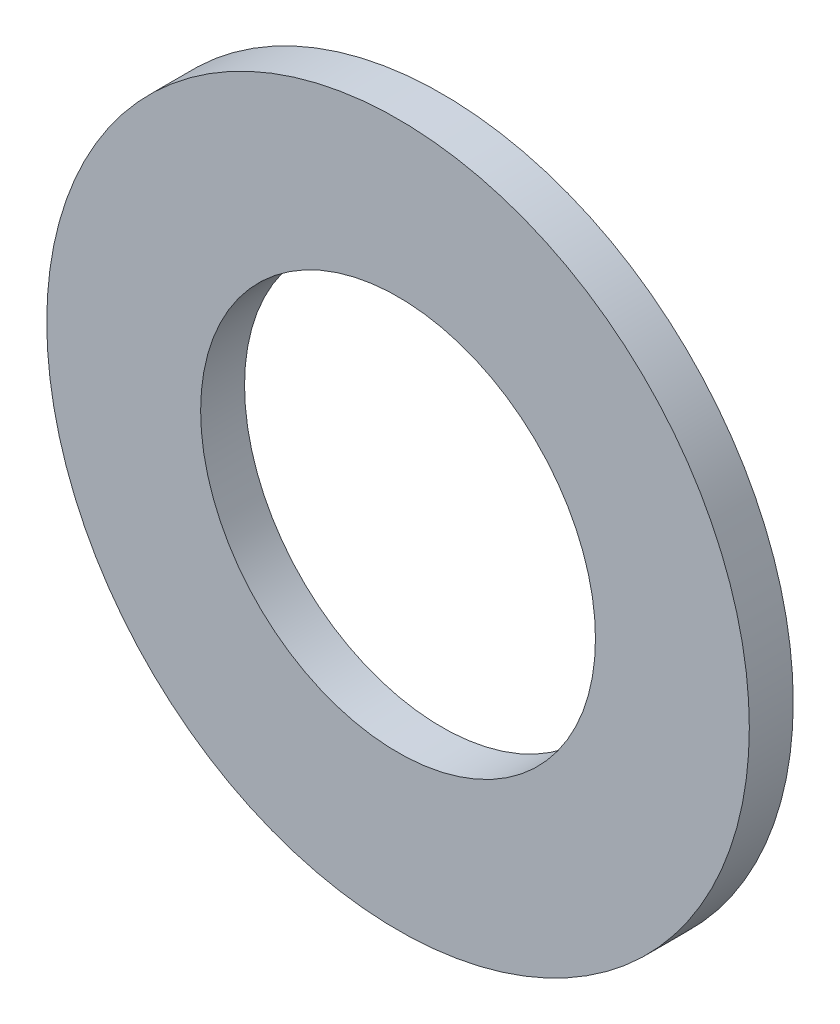
SolidWorks part; units mm, degrees
ref_plane "Front Plane" through (0, 0, 0) normal (0, 0, 1) x (1, 0, 0)
ref_plane "Top Plane" through (0, 0, 0) normal (0, 1, 0) x (1, 0, 0)
ref_plane "Right Plane" through (0, 0, 0) normal (1, 0, 0) x (0, 0, -1)
sketch "Sketch1" plane through (0, 0, 0) normal (0, 0, 1) x (1, 0, 0)
  line L0 (-7.1437, 0) -> (7.1437, 0) construction
  circle A0 centre (0, 0) radius 12.7 construction
  circle A1 centre (0, 0) radius 7.1374 construction
  dimension "OD" = 25.4
  dimension "ID" = 14.2748
  dimension "For Shaft Diameter" = 14.2875
sketch "Sketch2" plane through (0, 0, 0) normal (1, 0, 0) x (0, 0, -1)
  line L4 (0.7937, 12.7) -> (-0.7938, 12.7) construction
  point P0 (0, 12.7)
  dimension "Thickness" = 1.5875
sketch "Sketch3" plane through (0, 0, 0) normal (0, 0, 1) x (1, 0, 0)
  circle A0 centre (0, 0) radius 7.1374 construction
  circle A1 centre (0, 0) radius 12.7 construction
  circle A3 centre (0, 0) radius 7.1374
  circle A5 centre (0, 0) radius 12.7
extrude "Boss-Extrude1" add sketch "Sketch3" against normal up to vertex (0.7937 mm away) and the other way up to vertex (0.7937 mm away)
equation "\"D1\"= \"Thickness@Sketch2\""
